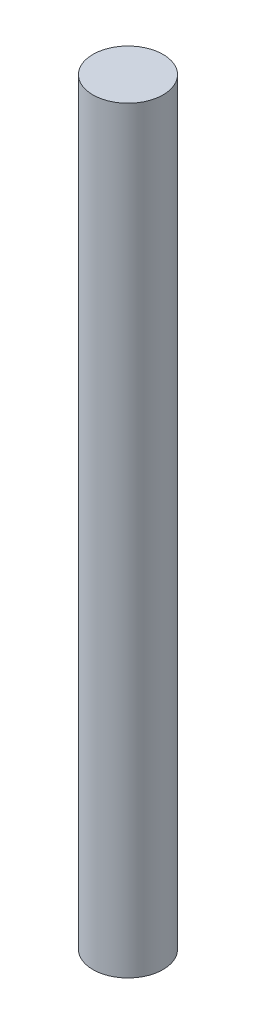
SolidWorks part; units mm, degrees
material "ABS"
ref_plane "Front Plane" through (0, 0, 0) normal (0, 0, 1) x (1, 0, 0)
ref_plane "Top Plane" through (0, 0, 0) normal (0, 1, 0) x (1, 0, 0)
ref_plane "Right Plane" through (0, 0, 0) normal (1, 0, 0) x (0, 0, -1)
sketch "Sketch1" plane through (0, 0, 0) normal (0, 1, 0) x (1, 0, 0)
  circle A0 centre (0, 0) radius 3.175
extrude "Boss-Extrude1" add sketch "Sketch1" along normal blind 68.58
